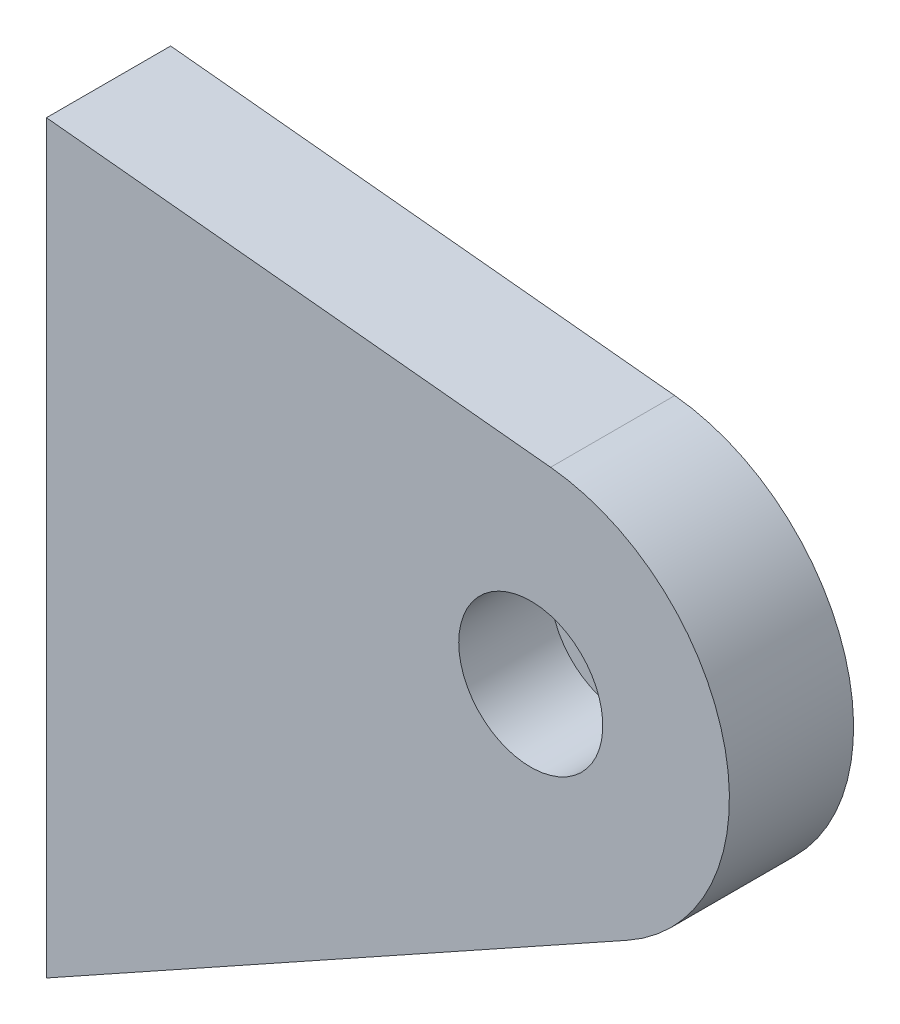
SolidWorks part; units mm, degrees
material "Alliage 1060"
ref_plane "Plan de face" through (0, 0, 0) normal (0, 0, 1) x (1, 0, 0)
ref_plane "Plan de dessus" through (0, 0, 0) normal (0, 1, 0) x (1, 0, 0)
ref_plane "Plan de droite" through (0, 0, 0) normal (1, 0, 0) x (0, 0, -1)
sketch "Esquisse1" plane through (0, 0, 0) normal (0, 0, 1) x (1, 0, 0)
  line L0 (0.8, 7.9599) -> (-19.5, 10)
  line L1 (3.8886, -6.9914) -> (-19.5, -20)
  line L3 (-19.5, -20) -> (-19.5, 10)
  arc A0 (0.8, 7.9599) -> (3.8886, -6.9914) centre (0, 0) cw
  circle A1 centre (0, 0) radius 1.5
  dimension "D5" = 3
  dimension "D1" = 8
  dimension "D2" = 10
  dimension "D3" = 19.5
  dimension "D4" = 30
extrude "Extrusion1" add sketch "Esquisse1" against normal blind 5
sketch "Esquisse2" plane through (0, 0, -3.7) normal (0, 0, -1) x (-1, 0, 0)
  circle A0 centre (0, 0) radius 2.9 construction
  circle A1 centre (0, 0) radius 2.9
extrude "Enlèv. mat.-Extru.1" cut sketch "Esquisse2" against normal through all
hole_wizard "Trou taraudé M3x0.51" positions "Esquisse4" profile "Esquisse3" tap size "M3x0.5" standard "Ansi Métrique"
sketch "Esquisse4" plane through (-19.5, 0, 0) normal (-1, 0, 0) x (0, 0, 1)
  circle A0 centre (-2.5, -16) radius 1.5 construction
  circle A1 centre (-2.5, 6) radius 1.5 construction
  point P0 (-2.5, 6)
  point P1 (-2.5, -16)
sketch "Esquisse3" plane through (-19.5, 6, -2.5) normal (0, 1, 0) x (0, 0, 1)
  line L0 (0, 0) -> (0, 9.8511)
  line L1 (0, 9.8511) -> (1.25, 9.1)
  line L2 (1.25, 9.1) -> (1.25, 0)
  line L5 (1.25, 0) -> (0, 0)
  line L10 (0, 9.8511) -> (-1.25, 9.1) construction
  line L11 (0, -6.35) -> (0, 107.95) construction
  dimension "Diamètre du trou pour taraudage" = 2.5
  dimension "Profondeur du trou pour taraudage" = 9.1
  dimension "Angle de pointe" = 118
cosmetic thread "Filetage de perçage1" parameters "D1"=7, "D2"=3
cosmetic thread "Filetage de perçage2" parameters "D1"=7, "D2"=3
